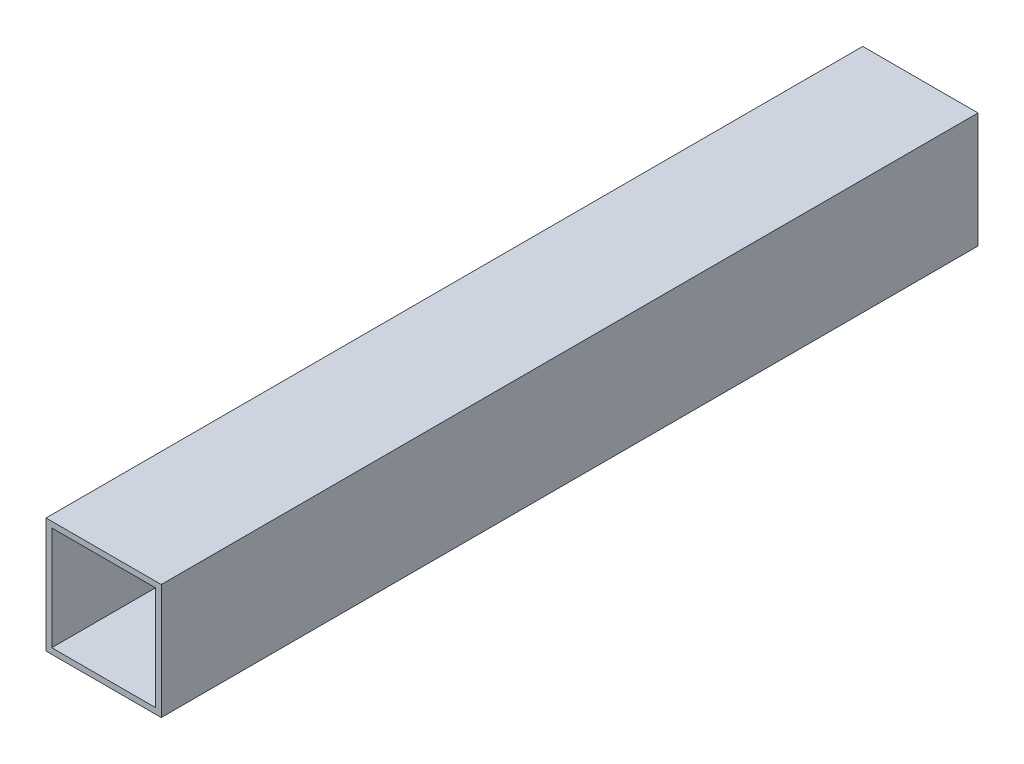
SolidWorks part; units mm, degrees
ref_plane "Front Plane" through (0, 0, 0) normal (0, 0, 1) x (1, 0, 0)
ref_plane "Top Plane" through (0, 0, 0) normal (0, 1, 0) x (1, 0, 0)
ref_plane "Right Plane" through (0, 0, 0) normal (1, 0, 0) x (0, 0, -1)
sketch "Sketch1" plane through (0, 0, 0) normal (0, 0, 1) x (1, 0, 0)
  line L5 (-15.875, 15.875) -> (15.875, 15.875)
  line L6 (-15.875, 15.875) -> (-15.875, -15.875)
  line L11 (-15.875, -15.875) -> (15.875, -15.875)
  line L12 (15.875, 15.875) -> (15.875, -15.875)
  line L13 (-15.875, 15.875) -> (15.875, -15.875) construction
  line L14 (-15.875, -15.875) -> (15.875, 15.875) construction
  line L15 (-14.2875, 14.2875) -> (14.2875, 14.2875)
  line L16 (-14.2875, 14.2875) -> (-14.2875, -14.2875)
  line L17 (-14.2875, -14.2875) -> (14.2875, -14.2875)
  line L18 (14.2875, 14.2875) -> (14.2875, -14.2875)
  line L19 (-14.2875, 14.2875) -> (14.2875, -14.2875) construction
  line L20 (-14.2875, -14.2875) -> (14.2875, 14.2875) construction
  point P0 (0, 0)
  point P6 (0, 0)
  dimension "D1" = 31.75
  dimension "D2" = 31.75
  dimension "D3" = 1.5875
extrude "Boss-Extrude1" add sketch "Sketch1" along normal blind 225
